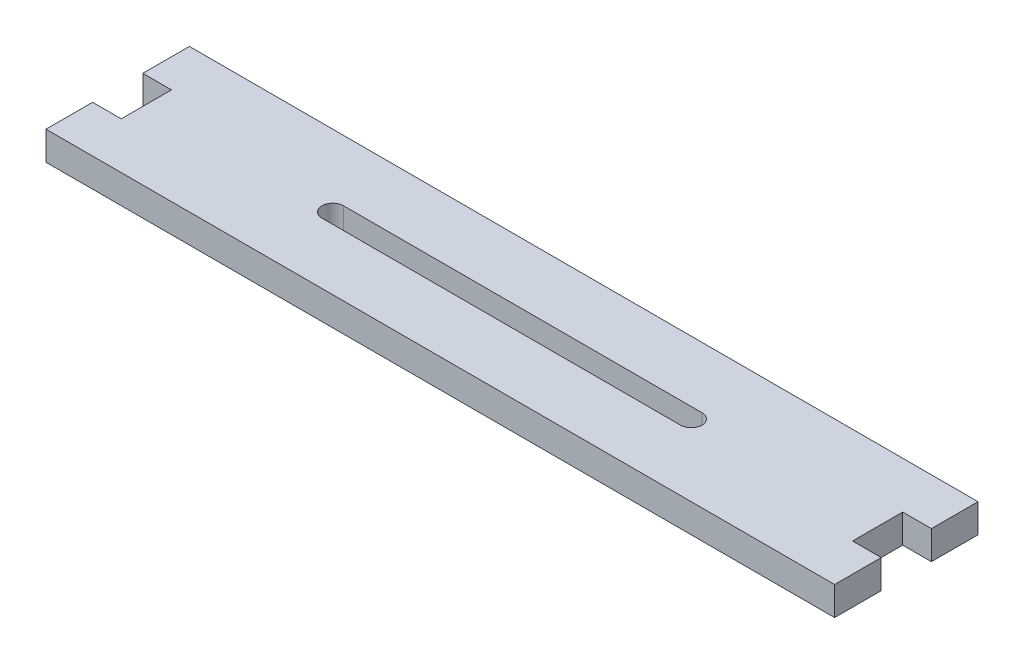
SolidWorks part; units mm, degrees
ref_plane "Front Plane" through (0, 0, 0) normal (0, 0, 1) x (1, 0, 0)
ref_plane "Top Plane" through (0, 0, 0) normal (0, 1, 0) x (1, 0, 0)
ref_plane "Right Plane" through (0, 0, 0) normal (1, 0, 0) x (0, 0, -1)
sketch "Sketch1" plane through (0, 0, 0) normal (0, 1, 0) x (1, 0, 0)
  line L0 (0, 10) -> (0, -10) construction
  line L1 (-55, 10) -> (55, 10)
  line L2 (-55, 10) -> (-55, -10)
  line L3 (-55, -10) -> (55, -10)
  line L4 (55, 10) -> (55, -10)
  line L5 (-55, 10) -> (55, -10) construction
  line L6 (-55, -10) -> (55, 10) construction
  line L7 (-55, -3.5) -> (-51, -3.5)
  line L8 (-55, -3.5) -> (-55, 3.5)
  line L9 (-55, 3.5) -> (-51, 3.5)
  line L10 (-51, -3.5) -> (-51, 3.5)
  line L11 (55, -3.5) -> (51, -3.5)
  line L12 (51, -3.5) -> (51, 3.5)
  line L13 (55, 3.5) -> (51, 3.5)
  point P0 (0, 0)
  dimension "D1" = 110
  dimension "D2" = 20
  dimension "D3" = 6.5
  dimension "D4" = 6.5
  dimension "D5" = 4
extrude "Boss-Extrude1" add sketch "Sketch1" along normal blind 4 contours L13 L4 L1 L2 L9 L10 L7 L3 L11 L12
sketch "Sketch2" plane through (0, 0, 0) normal (0, -1, 0) x (1, 0, 0)
  line L0 (-25, -1.5) -> (25, -1.5)
  line L1 (-25, 1.5) -> (25, 1.5)
  circle A0 centre (25, 0) radius 1.5
  circle A1 centre (-25, 0) radius 1.5
  point P8 (0, 0)
  point P12 (0, 0)
  dimension "D1" = 3
  dimension "D2" = 25
  dimension "D3" = 25
extrude "Cut-Extrude2" cut sketch "Sketch2" against normal blind 4 contours A1 L0 A0 L1 | A1 | A0
equation "\"D4@Sketch1\"=\"D3@Sketch1\""
equation "\"D3@Sketch2\"=\"D2@Sketch2\""
